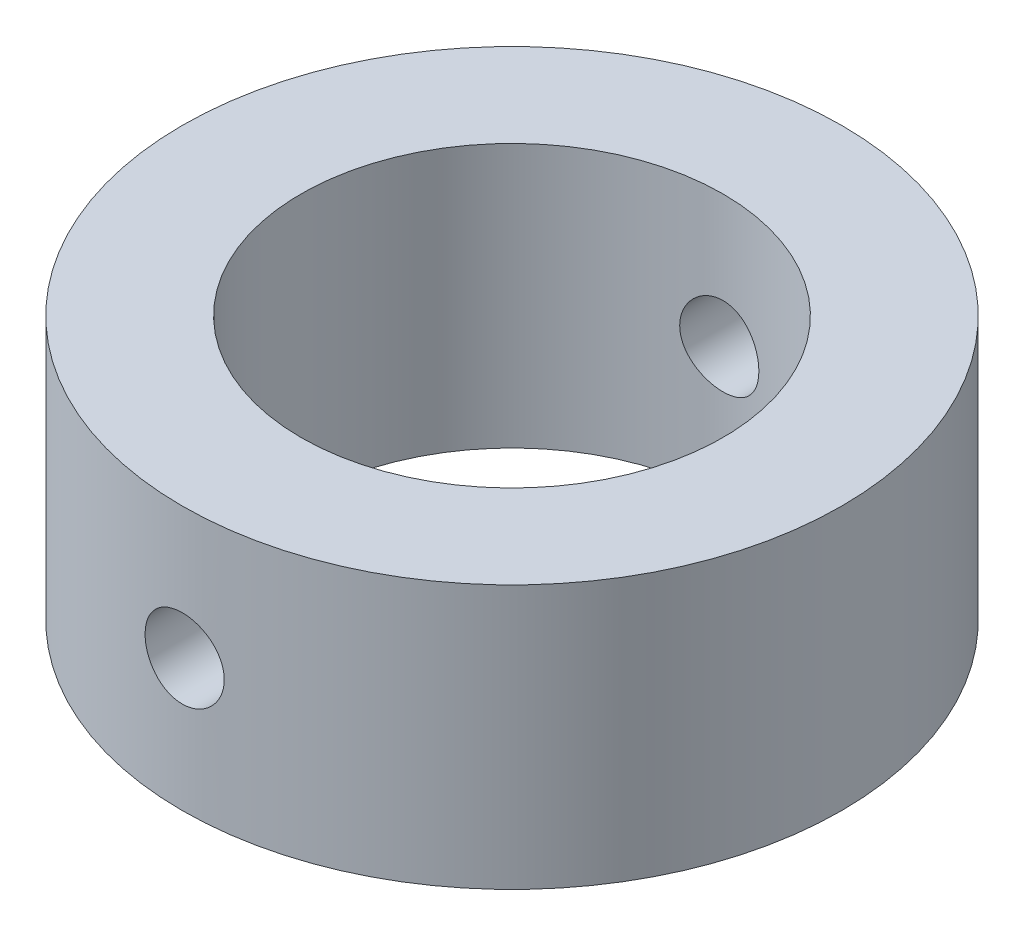
SolidWorks part; units mm, degrees
ref_plane "Front Plane" through (0, 0, 0) normal (0, 0, 1) x (1, 0, 0)
ref_plane "Top Plane" through (0, 0, 0) normal (0, 1, 0) x (1, 0, 0)
ref_plane "Right Plane" through (0, 0, 0) normal (1, 0, 0) x (0, 0, -1)
sketch "Sketch2" plane through (0, 0, 0) normal (0, 1, 0) x (1, 0, 0)
  circle A0 centre (0, 0) radius 8
  circle A1 centre (0, 0) radius 12.5
  dimension "D1" = 16
  dimension "D2" = 4.5
extrude "Boss-Extrude1" add sketch "Sketch2" along normal blind 10
sketch "Sketch3" plane through (0, 0, 0) normal (0, 0, 1) x (1, 0, 0)
  line L0 (-12.5, 10) -> (-12.5, 0) construction
  line L1 (-12.5, 0) -> (12.5, 0) construction
  line L2 (12.5, 0) -> (12.5, 10) construction
  line L3 (12.5, 10) -> (-12.5, 10) construction
  line L4 (-12.5, 10) -> (-12.5, 0)
  line L5 (-12.5, 0) -> (12.5, 0)
  line L6 (12.5, 0) -> (12.5, 10)
  line L7 (12.5, 10) -> (-12.5, 10)
  line L8 (0, 10) -> (0, 0) construction
  line L9 (-12.5, 5) -> (12.5, 5) construction
  circle A0 centre (0, 5) radius 1.5
  dimension "D1" = 3
extrude "Cut-Extrude1" cut sketch "Sketch3" against normal through all both and the other way through all contours A0
